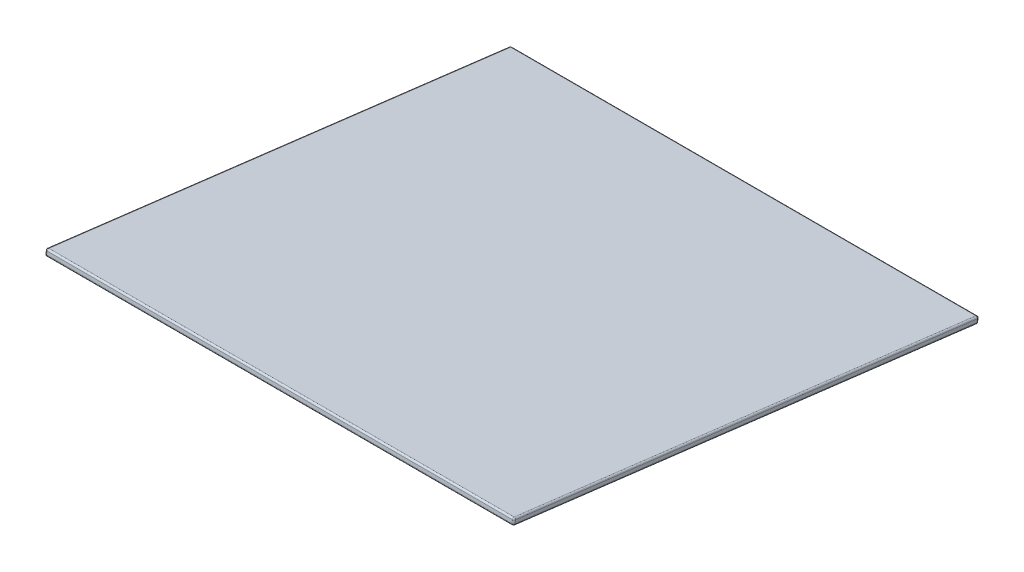
SolidWorks part; units mm, degrees
ref_plane "Plano frontal" through (0, 0, 0) normal (0, 0, 1) x (1, 0, 0)
ref_plane "Plano superior" through (0, 0, 0) normal (0, 1, 0) x (1, 0, 0)
ref_plane "Plano direito" through (0, 0, 0) normal (1, 0, 0) x (0, 0, -1)
sketch "Sketch1" plane through (0, -4.6496, 0.5709) normal (0, 0.9925, -0.1219) x (1, 0, 0)
  line L1 (72.5, 72.5) -> (-72.5, 72.5)
  line L2 (72.5, 72.5) -> (72.5, -72.5)
  line L3 (72.5, -72.5) -> (-72.5, -72.5)
  line L4 (-72.5, 72.5) -> (-72.5, -72.5)
  line L5 (72.5, 72.5) -> (-72.5, -72.5) construction
  line L6 (72.5, -72.5) -> (-72.5, 72.5) construction
  point P0 (0, 0)
  dimension "D1" = 145
  dimension "D2" = 145
extrude "Boss-Extrude1" add sketch "Sketch1" along normal blind 2 contours L1 L4 L3 L2
fillet "Fillet1" radius 0.5 12 edges at (0, -11.5001, -71.6324) (0, -13.4851, -71.3887) (72.5, -2.6645, 0.3272) (72.5, -12.4926, -71.5106) (72.5, -4.6496, 0.5709) (-72.5, -12.4926, -71.5106) (-72.5, -2.6645, 0.3272) (-72.5, -4.6496, 0.5709) (-72.5, 5.1785, 72.4086) (0, 6.171, 72.2868) (72.5, 5.1785, 72.4086) (0, 4.1859, 72.5305)
